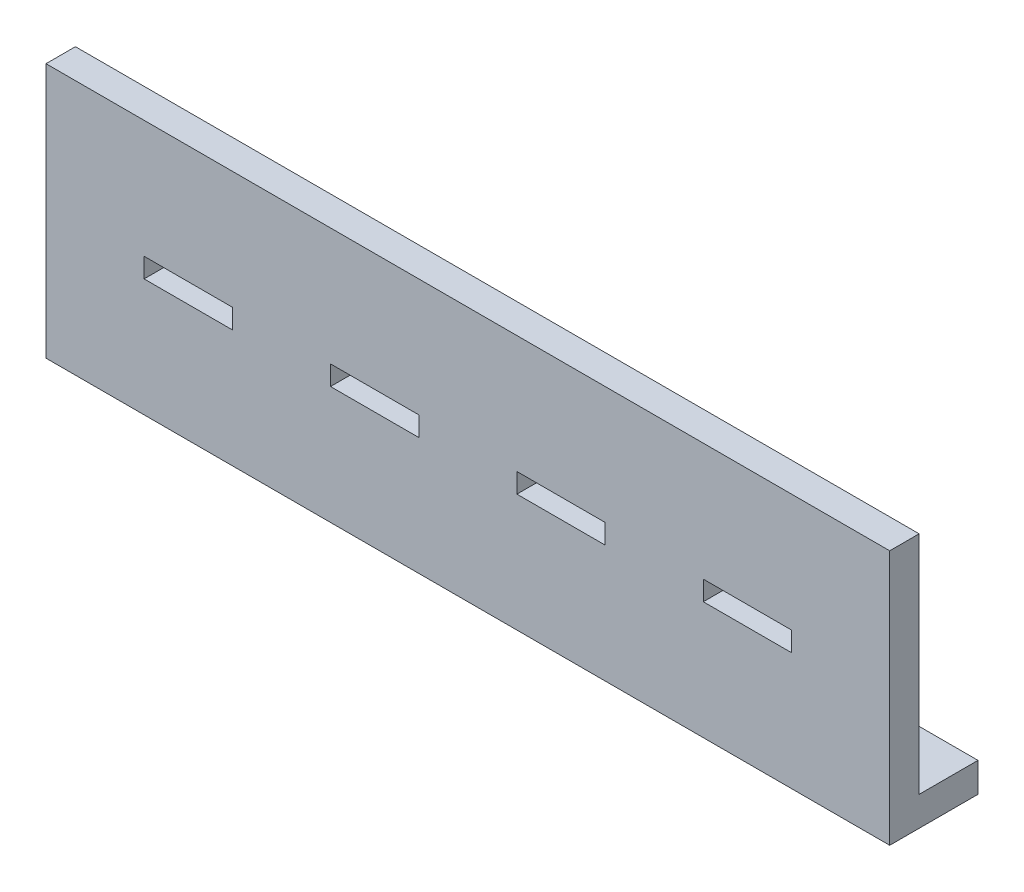
SolidWorks part; units mm, degrees
ref_plane "前视基准面" through (0, 0, 0) normal (0, 0, 1) x (1, 0, 0)
ref_plane "上视基准面" through (0, 0, 0) normal (0, 1, 0) x (1, 0, 0)
ref_plane "右视基准面" through (0, 0, 0) normal (1, 0, 0) x (0, 0, -1)
sketch "草图1" plane through (0, 0, 0) normal (0, 0, 1) x (1, 0, 0)
  line L3 (0, 0) -> (86, 0)
  line L4 (0, 0) -> (0, 26)
  line L5 (0, 26) -> (86, 26)
  line L6 (86, 0) -> (86, 26)
  line L7 (10, 14) -> (19, 14)
  line L8 (10, 14) -> (10, 12)
  line L9 (10, 12) -> (19, 12)
  line L10 (19, 14) -> (19, 12)
  line L11 (29, 14) -> (38, 14)
  line L12 (29, 14) -> (29, 12)
  line L13 (29, 12) -> (38, 12)
  line L14 (38, 14) -> (38, 12)
  line L15 (48, 14) -> (57, 14)
  line L16 (48, 14) -> (48, 12)
  line L17 (48, 12) -> (57, 12)
  line L18 (57, 14) -> (57, 12)
  line L19 (67, 14) -> (76, 14)
  line L20 (67, 14) -> (67, 12)
  line L21 (67, 12) -> (76, 12)
  line L22 (76, 14) -> (76, 12)
  dimension "D1" = 86
  dimension "D2" = 26
extrude "凸台-拉伸1" add sketch "草图1" along normal mid plane 3
sketch "草图3" plane through (0, 0, -1.5) normal (0, 0, -1) x (-1, 0, 0)
  line L0 (-86, 3) -> (-86, 0)
  line L1 (-86, 0) -> (-86, 26) construction
  line L2 (55, 0) -> (-55, 0) construction
  line L3 (-86, 0) -> (0, 0)
  line L4 (0, 0) -> (0, 3)
  line L5 (0, 55) -> (0, -55) construction
  line L6 (0, 3) -> (-86, 3)
extrude "凸台-拉伸2" add sketch "草图3" along normal blind 6
sketch "草图4" plane through (0, 3, 0) normal (0, 1, 0) x (1, 0, 0)
  circle A0 centre (10, 4.5) radius 2
  circle A1 centre (76, 4.5) radius 2
extrude "切除-拉伸1" cut sketch "草图4" against normal blind 6
